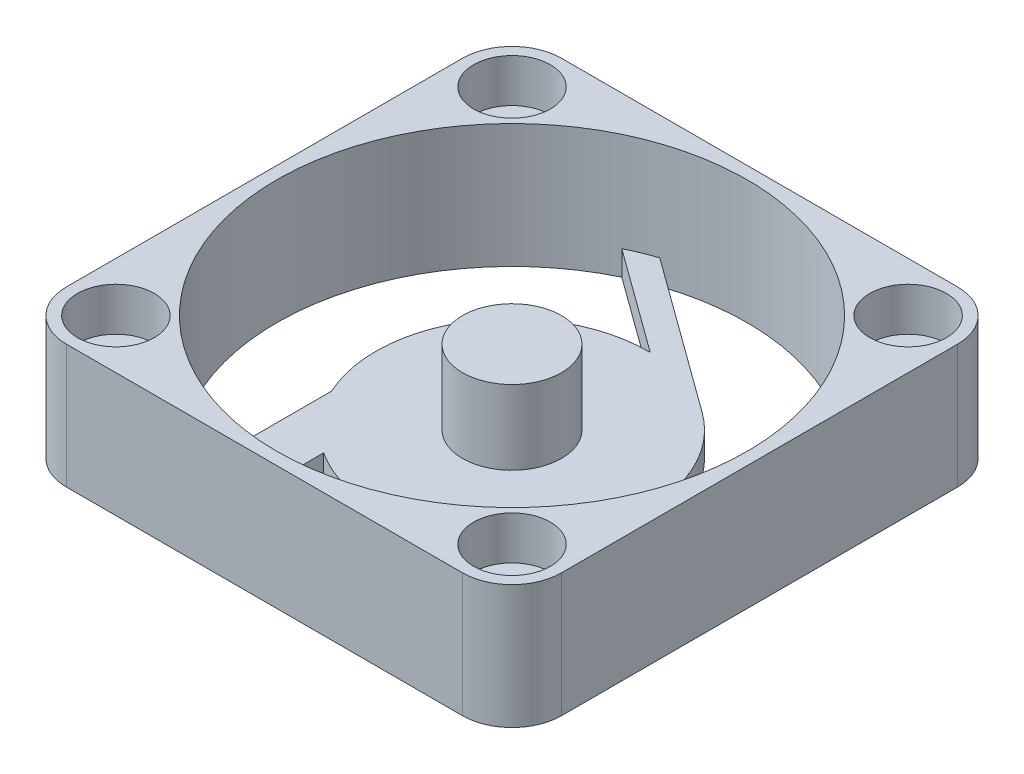
SolidWorks part; units mm, degrees
ref_plane "Спереди" through (0, 0, 0) normal (0, 0, 1) x (1, 0, 0)
ref_plane "Сверху" through (0, 0, 0) normal (0, 1, 0) x (1, 0, 0)
ref_plane "Справа" through (0, 0, 0) normal (1, 0, 0) x (0, 0, -1)
sketch "Эскиз1" plane through (0, 0, 0) normal (0, 1, 0) x (1, 0, 0)
  line L1 (16, -20) -> (-16, -20)
  line L2 (20, -16) -> (20, 16)
  line L3 (16, 20) -> (-16, 20)
  line L4 (-20, -16) -> (-20, 16)
  line L5 (20, -20) -> (-20, 20) construction
  line L6 (20, 20) -> (-20, -20) construction
  arc A0 (-16, -20) -> (-20, -16) centre (-16, -16) cw
  arc A1 (16, -20) -> (20, -16) centre (16, -16) ccw
  arc A2 (20, 16) -> (16, 20) centre (16, 16) ccw
  arc A3 (-16, 20) -> (-20, 16) centre (-16, 16) ccw
  point P0 (0, 0)
  dimension "D3" = 4
  dimension "D1" = 40
  dimension "D2" = 40
extrude "Бобышка-Вытянуть1" add sketch "Эскиз1" along normal blind 10
sketch "Эскиз2" plane through (0, 10, 0) normal (0, 1, 0) x (1, 0, 0)
  circle A0 centre (0, 0) radius 19
  dimension "D1" = 38
extrude "Вырез-Вытянуть1" cut sketch "Эскиз2" against normal blind 8
sketch "Эскиз3" plane through (0, 2, 0) normal (0, 1, 0) x (1, 0, 0)
  line L0 (-10, 22.0697) -> (-10, -21.8154) construction
  line L1 (-6, 22.0697) -> (-6, -21.8154) construction
  line L2 (-10, -4.5826) -> (-10, -16.1555)
  line L3 (-6, -9.2195) -> (-6, -18.0278)
  line L4 (6.4656, 8.8992) -> (-6.0676, 18.0051)
  line L5 (-8.2474, 17.1167) -> (0.1734, 10.9986)
  line L6 (5.5, -9.5263) -> (18.9164, -1.7803)
  line L7 (18.9914, 0.5724) -> (9.9772, -4.632)
  line L10 (-16, -20) -> (16, -20) construction
  arc A0 (0.1734, 10.9986) -> (-10, -4.5826) centre (0, 0) ccw
  arc A1 (-8.2474, 17.1167) -> (-10, -16.1555) centre (0, 0) ccw
  arc A2 (18.9914, 0.5724) -> (-6.0676, 18.0051) centre (0, 0) ccw
  arc A3 (9.9772, -4.632) -> (6.4656, 8.8992) centre (0, 0) ccw
  arc A4 (-6, -9.2195) -> (5.5, -9.5263) centre (0, 0) ccw
  arc A5 (-6, -18.0278) -> (18.9164, -1.7803) centre (0, 0) ccw
  dimension "D1" = 22
  dimension "D4" = 38
  dimension "D2" = 10
  dimension "D3" = 6
  dimension "D5" = 8.2474
  dimension "D6" = 10.9986
  dimension "D7" = 6.4656
  dimension "D8" = 9.9772
  dimension "D9" = 20.5724
extrude "Вырез-Вытянуть2" cut sketch "Эскиз3" against normal blind 9
sketch "Эскиз4" plane through (0, 10, 0) normal (0, 1, 0) x (1, 0, 0)
  line L0 (-20, 16) -> (-20, -16) construction
  line L1 (-16, -20) -> (16, -20) construction
  line L2 (16, 20) -> (-16, 20) construction
  line L3 (20, -16) -> (20, 16) construction
  circle A0 centre (-16, 16) radius 1.75
  circle A1 centre (16, 16) radius 1.75
  circle A2 centre (-16, -16) radius 1.75
  circle A3 centre (16, -16) radius 1.75
  dimension "D1" = 4
  dimension "D3" = 3.5
  dimension "D6" = 3.5
  dimension "D9" = 3.5
  dimension "D12" = 3.5
  dimension "D2" = 4
  dimension "D4" = 4
  dimension "D5" = 4
  dimension "D7" = 4
  dimension "D8" = 4
  dimension "D10" = 4
  dimension "D11" = 4
extrude "Вырез-Вытянуть3" cut sketch "Эскиз4" against normal through all
sketch "Эскиз5" plane through (0, 10, 0) normal (0, 1, 0) x (1, 0, 0)
  circle A0 centre (-16, 16) radius 3.1
  circle A1 centre (16, 16) radius 3.1
  circle A2 centre (16, -16) radius 3.1
  circle A3 centre (-16, -16) radius 3.1
  dimension "D1" = 6.2
  dimension "D2" = 6.2
  dimension "D3" = 6.2
  dimension "D4" = 6.2
extrude "Вырез-Вытянуть4" cut sketch "Эскиз5" against normal blind 3.5
sketch "Эскиз6" plane through (0, 2, 0) normal (0, 1, 0) x (1, 0, 0)
  circle A0 centre (0, 0) radius 4
  dimension "D1" = 8
extrude "Бобышка-Вытянуть2" add sketch "Эскиз6" along normal blind 6
